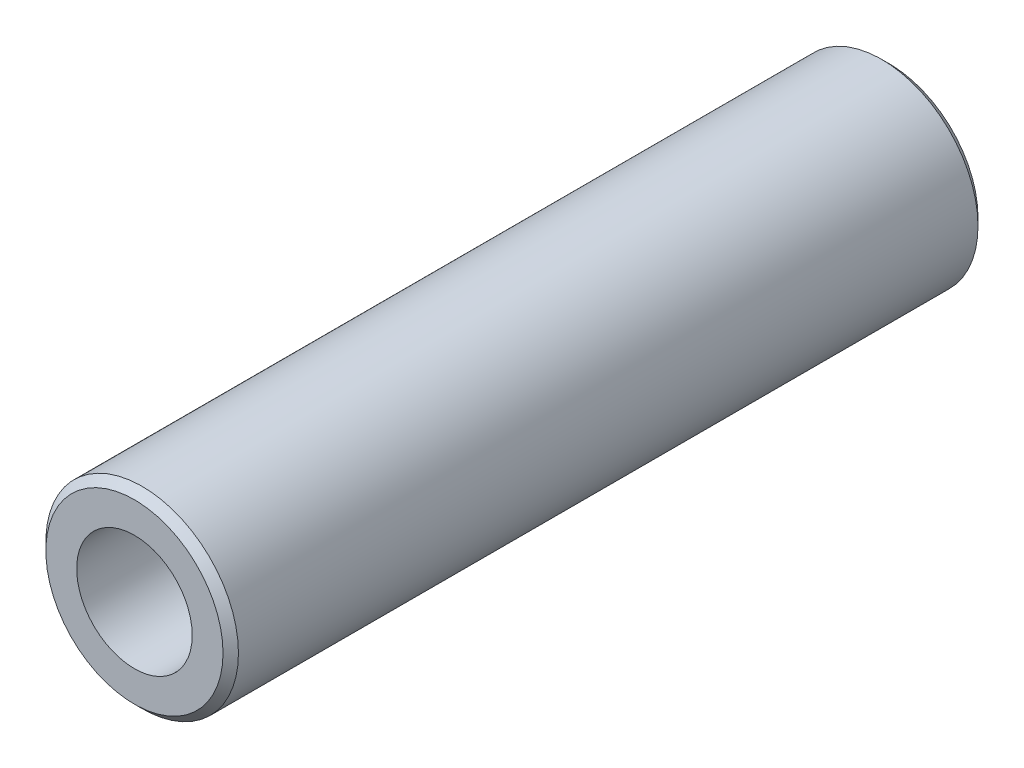
SolidWorks part; units mm, degrees
ref_plane "Front Plane" through (0, 0, 0) normal (0, 0, 1) x (1, 0, 0)
ref_plane "Top Plane" through (0, 0, 0) normal (0, 1, 0) x (1, 0, 0)
ref_plane "Right Plane" through (0, 0, 0) normal (1, 0, 0) x (0, 0, -1)
sketch "Sketch1" plane through (0, 0, 0) normal (0, 0, 1) x (1, 0, 0)
  circle A0 centre (0, 0) radius 6.25
  dimension "D1" = 12.5
extrude "Extrude-Thin1" add sketch "Sketch1" along normal mid plane 49 thin contours A0 thin type one direction reverse wall 2.5
chamfer "Chamfer1" distance 0.5 angle 45 2 edges at (6.25, 0, -24.5) (6.25, 0, 24.5)
